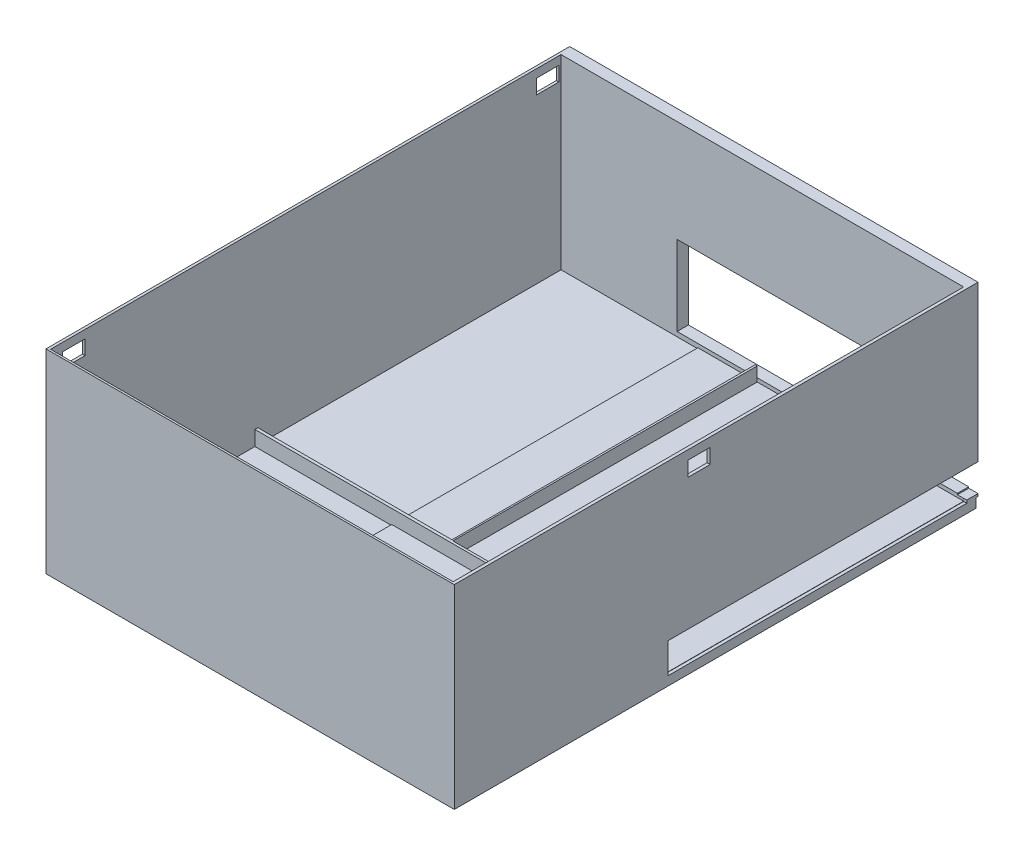
SolidWorks part; units mm, degrees
ref_plane "Front Plane" through (0, 0, 0) normal (0, 0, 1) x (1, 0, 0)
ref_plane "Top Plane" through (0, 0, 0) normal (0, 1, 0) x (1, 0, 0)
ref_plane "Right Plane" through (0, 0, 0) normal (1, 0, 0) x (0, 0, -1)
sketch "Sketch1" plane through (0, 0, 0) normal (0, 1, 0) x (1, 0, 0)
  line L1 (-37.1465, 32.3865) -> (39.0132, 32.3865)
  line L2 (-37.1465, 32.3865) -> (-37.1465, -94.5463)
  line L3 (-37.1465, -94.5463) -> (39.0132, -94.5463)
  line L4 (39.0132, 32.3865) -> (39.0132, -94.5463)
  dimension "D1" = 39.0132
  dimension "D2" = 37.1465
  dimension "D3" = 32.3865
  dimension "D4" = 94.5463
extrude "Boss-Extrude1" add sketch "Sketch1" along normal blind 2.54
sketch "Sketch2" plane through (0, 0, 0) normal (0, 1, 0) x (1, 0, 0)
  line L0 (-17.1137, 32.3865) -> (-19.5757, 32.3865)
  line L1 (-19.5757, 32.3865) -> (-19.5757, -53.9937)
  line L2 (39.0132, 32.3865) -> (-37.1465, 32.3865) construction
  line L3 (-19.5757, -53.9937) -> (39.0132, -53.9937)
  line L4 (-17.1137, 32.3865) -> (-17.1137, -51.9925)
  line L5 (39.0132, -51.9925) -> (-17.1137, -51.9925)
  line L6 (39.0132, -94.5463) -> (39.0132, 32.3865) construction
  line L7 (39.0132, -94.5463) -> (39.0132, 32.3865) construction
  line L8 (39.0132, -53.9937) -> (39.0132, -51.9925)
  dimension "D1" = 17.1137
  dimension "D2" = 19.5757
  dimension "D3" = 51.9925
  dimension "D4" = 53.9937
sketch "Sketch7" plane through (0, 2.54, 0) normal (0, 1, 0) x (1, 0, 0)
  line L0 (-37.1465, 32.3865) -> (-37.1465, -94.5463)
  line L1 (-37.1465, -94.5463) -> (39.0132, -94.5463)
  line L2 (39.0132, -94.5463) -> (39.0132, 32.3865)
  line L4 (-37.1465, 32.3865) -> (-37.1465, 37.5149)
  line L5 (39.0132, 37.5149) -> (39.0132, 32.3865)
  line L6 (39.0132, 37.5149) -> (-37.1465, 37.5149)
  dimension "D1" = 132.0612
extrude "Boss-Extrude4" add sketch "Sketch7" along normal blind 38.1
shell "Shell1" thickness 2.54
sketch "Sketch12" plane through (0, 0, 0) normal (0, 1, 0) x (1, 0, 0)
  line L14 (-19.5757, -53.9937) -> (39.0132, -53.9937) construction
  line L15 (-17.7524, -53.9937) -> (39.0132, -53.9937)
  line L17 (39.0132, -53.9937) -> (39.0132, -53.3287)
  line L18 (39.0132, -53.9937) -> (39.0132, -51.9925) construction
  line L25 (39.0132, -53.3287) -> (-17.7524, -53.3287)
  line L27 (-18.2815, -53.9937) -> (-17.7524, -53.9937)
  line L28 (-17.7524, -53.3287) -> (-18.5357, -53.3287)
  line L29 (-18.5357, -53.3287) -> (-18.3447, 32.3865)
  line L30 (-17.1137, 32.3865) -> (-19.5757, 32.3865) construction
  line L31 (-18.3447, 32.3865) -> (-18.928, 32.3865)
  line L32 (-18.928, 32.3865) -> (-18.928, -53.9937)
  line L33 (-18.928, -53.9937) -> (-18.2815, -53.9937)
  dimension "D1" = 17.7524
  dimension "D2" = 18.2815
  dimension "D3" = 18.5357
  dimension "D4" = 18.928
  dimension "D5" = 53.3287
extrude "Boss-Extrude5" add sketch "Sketch12" along normal blind 6.35
ref_plane "Plane3" through (0, 0, -40.0549) normal (0, 0, -1) x (-1, 0, 0)
sketch "Sketch16" plane through (0, 0, -40.0549) normal (0, 0, -1) x (-1, 0, 0)
  line L0 (-39.0132, 40.64) -> (-39.0132, 0)
  line L1 (-39.0132, 0) -> (37.1465, 0)
  line L2 (-39.0132, 40.64) -> (37.1465, 40.64)
  line L3 (37.1465, 40.64) -> (37.1465, 0)
extrude "Cut-Extrude7" cut sketch "Sketch16" against normal blind 7.112
ref_plane "Plane4" through (0, 7.62, 0) normal (0, 1, 0) x (1, 0, 0)
sketch "Sketch17" plane through (0, 7.62, 0) normal (0, 1, 0) x (1, 0, 0)
  line L0 (-34.6065, 32.9429) -> (-34.6065, 29.8465)
  line L1 (-34.6065, 29.8465) -> (36.4732, 29.8465)
  line L2 (36.4732, 29.8465) -> (36.4732, 32.9429)
  line L3 (36.4732, 32.9429) -> (-34.6065, 32.9429)
extrude "Cut-Extrude8" cut sketch "Sketch17" against normal blind 4.064
sketch "Sketch19" plane through (0, 0, 0) normal (0, 1, 0) x (1, 0, 0)
  line L3 (-37.1465, 32.9429) -> (-37.1465, -94.5463)
  line L5 (-72.7979, 32.9429) -> (-72.7979, -94.5463)
  line L8 (-72.7979, -94.5463) -> (-37.1465, -94.5463)
  line L9 (-72.7979, 32.9429) -> (-37.1465, 32.9429)
  dimension "D2" = 72.7979
extrude "Boss-Extrude19" add sketch "Sketch19" along normal blind 2.286
ref_plane "Plane5" through (-39.6865, 0, 0) normal (-1, 0, 0) x (0, 0, 1)
sketch "Sketch26" plane through (-37.1465, 0, 0) normal (-1, 0, 0) x (0, 0, 1)
  line L1 (-32.9429, 40.64) -> (94.5463, 40.64)
  line L2 (-32.9429, 40.64) -> (-32.9429, 2.286)
  line L3 (-32.9429, 2.286) -> (94.5463, 2.286)
  line L4 (94.5463, 40.64) -> (94.5463, 2.286)
extrude "Cut-Extrude10" cut sketch "Sketch26" against normal blind 2.54
sketch "Sketch27" plane through (0, 0, 0) normal (0, 1, 0) x (1, 0, 0)
  line L0 (-34.6065, -94.5463) -> (-72.7979, -94.5463)
  line L1 (-72.7979, -94.5463) -> (-72.7979, 32.9429)
  line L2 (-34.6065, -94.5463) -> (-34.6065, -92.0063)
  line L4 (-34.6065, 29.8465) -> (-34.6065, -92.0063) construction
  line L5 (-34.6065, 32.3865) -> (-34.6065, -94.5463) construction
  line L6 (-34.6065, -92.0063) -> (-70.1044, -92.0063)
  line L8 (-72.7979, 32.9429) -> (-34.6065, 32.9429)
  line L10 (-34.6065, 29.8465) -> (-34.6065, 32.9429)
  line L11 (-34.6065, 29.8465) -> (-72.0805, 29.8465)
  line L12 (-72.0805, 29.8465) -> (-72.0805, -92.0063)
  line L13 (-72.0805, -92.0063) -> (-70.1044, -92.0063)
  dimension "D1" = 70.1044
  dimension "D2" = 72.0805
  dimension "D3" = 92.0063
  dimension "D4" = 29.8465
extrude "Boss-Extrude20" add sketch "Sketch27" along normal blind 40.64
sketch "Sketch28" plane through (0, 0, 0) normal (0, 1, 0) x (1, 0, 0)
  line L3 (-72.7979, -94.5463) -> (39.0132, -94.5463)
  line L6 (39.0132, -94.5463) -> (39.0132, -110.4832)
  line L11 (39.0132, -110.4832) -> (-72.7979, -110.4832)
  line L12 (-72.7979, -110.4832) -> (-72.7979, -94.5463)
  dimension "D2" = 110.4832
extrude "Boss-Extrude21" add sketch "Sketch28" along normal blind 2.54
ref_plane "Plane10" through (0, 0, 97.0863) normal (0, 0, 1) x (1, 0, 0)
sketch "Sketch34" plane through (0, 0, 97.0863) normal (0, 0, 1) x (1, 0, 0)
  line L1 (-72.7979, 40.64) -> (39.0132, 40.64)
  line L2 (-72.7979, 40.64) -> (-72.7979, 2.54)
  line L3 (-72.7979, 2.54) -> (39.0132, 2.54)
  line L4 (39.0132, 40.64) -> (39.0132, 2.54)
extrude "Cut-Extrude12" cut sketch "Sketch34" against normal blind 5.08
sketch "Sketch36" plane through (0, 0, 0) normal (0, 1, 0) x (1, 0, 0)
  line L0 (-72.7979, -92.0063) -> (-72.7979, -110.4832)
  line L1 (-72.7979, -110.4832) -> (39.0132, -110.4832)
  line L2 (39.0132, -110.4832) -> (39.0132, -92.0063)
  line L3 (39.0132, -92.0063) -> (36.4732, -92.0063)
  line L6 (36.4732, -92.0063) -> (36.4732, -108.8333)
  line L7 (36.4732, -108.8333) -> (-72.0805, -108.8333)
  line L8 (-72.0805, -92.0063) -> (-72.0805, -108.8333)
  line L9 (-72.7979, -92.0063) -> (-72.0805, -92.0063)
  dimension "D1" = 108.8333
extrude "Boss-Extrude23" add sketch "Sketch36" along normal blind 40.64
sketch "Sketch39" plane through (0, 0, 0) normal (0, 1, 0) x (1, 0, 0)
  line L0 (-19.5757, -53.9937) -> (-72.0805, -53.9937)
  line L1 (-72.0805, -53.9937) -> (-72.0805, -53.1862)
  line L2 (-72.0805, -92.0063) -> (-72.0805, 29.8465) construction
  line L7 (-72.0805, -108.8333) -> (-72.0805, 29.8465) construction
  line L8 (-72.0805, -53.1862) -> (-19.5757, -53.1862)
  line L9 (-19.5757, 32.3865) -> (-19.5757, -53.9937) construction
  line L22 (-19.5757, -53.9937) -> (-18.928, -53.9937)
  line L23 (-19.5757, -53.1862) -> (-18.928, -53.1862)
  line L25 (-18.928, 29.8465) -> (-18.928, -53.9937) construction
  line L26 (-18.928, -53.1862) -> (-18.928, -53.9937)
  dimension "D1" = 53.1862
extrude "Boss-Extrude24" add sketch "Sketch39" along normal blind 6.35
sketch "Sketch51" plane through (0, 40.64, 0) normal (0, 1, 0) x (1, 0, 0)
  line L0 (-34.6065, 32.9429) -> (-34.6065, 29.8465)
  line L1 (-34.6065, 29.8465) -> (-72.0805, 29.8465)
  line L2 (-72.0805, 29.8465) -> (-72.0805, -108.8333)
  line L6 (39.0132, 32.9429) -> (39.0132, -110.4832)
  line L7 (39.0132, -110.4832) -> (-72.7979, -110.4832)
  line L8 (-72.7979, -110.4832) -> (-72.7979, 32.9429)
  line L9 (-72.7979, 32.9429) -> (-34.6065, 32.9429)
  line L10 (39.0132, 32.9429) -> (38.1798, 32.9429)
  line L11 (36.4732, 32.9429) -> (39.0132, 32.9429) construction
  line L12 (38.1798, -109.5531) -> (38.1798, 32.9429)
  line L14 (-72.0805, -109.5531) -> (-72.0805, -108.8333)
  line L16 (-72.0805, -109.5531) -> (-72.0805, -109.9497)
  line L17 (-72.0805, -109.9497) -> (38.1798, -109.9497)
  line L18 (38.1798, -109.9497) -> (38.1798, -109.5531)
  dimension "D1" = 1.7066
  dimension "D2" = 142.496
  dimension "D3" = 142.8926
extrude "Boss-Extrude28" add sketch "Sketch51" along normal blind 12.7
sketch "Sketch52" plane through (0, 53.34, 0) normal (0, 1, 0) x (1, 0, 0)
  line L1 (-34.6065, 32.9429) -> (-72.7979, 32.9429) construction
  line L2 (-34.6065, 29.8465) -> (-34.6065, 32.9429) construction
  line L8 (38.1798, 32.9429) -> (38.1798, 29.8465)
  line L9 (38.1798, 32.9429) -> (38.1798, -109.9497) construction
  line L11 (38.1798, 32.9429) -> (-34.6065, 32.9429)
  line L12 (-34.6065, 29.8465) -> (38.1798, 29.8465)
  line L13 (-34.6065, 32.9429) -> (-39.7253, 32.9429)
  line L14 (-39.7253, 32.9429) -> (-39.7253, 29.8465)
  line L15 (-72.0805, 29.8465) -> (-34.6065, 29.8465) construction
  line L16 (-39.7253, 29.8465) -> (-34.6065, 29.8465)
  line L17 (39.0132, -110.4832) -> (39.0132, 32.9429) construction
  dimension "D1" = 78.7385
extrude "Boss-Extrude29" add sketch "Sketch52" against normal blind 27.94
ref_plane "Plane15" through (-75.3379, 0, 0) normal (-1, 0, 0) x (0, 0, 1)
sketch "Sketch54" plane through (-72.7979, 0, 0) normal (-1, 0, 0) x (0, 0, 1)
  line L0 (100.4953, 51.0887) -> (100.4953, 47.1068)
  line L1 (-29.2744, 51.0887) -> (-23.0672, 51.0887)
  line L2 (-29.2744, 51.0887) -> (-29.2744, 47.1068)
  line L3 (-29.2744, 47.1068) -> (-23.0672, 47.1068)
  line L4 (-23.0672, 51.0887) -> (-23.0672, 47.1068)
  line L5 (100.4953, 47.1068) -> (106.7025, 47.1068)
  line L6 (100.4953, 51.0887) -> (106.7025, 51.0887)
  line L7 (106.7025, 51.0887) -> (106.7025, 47.1068)
  line L8 (110.4832, 53.34) -> (110.4832, 0) construction
  line L11 (-32.9429, 53.34) -> (-32.9429, 0) construction
  line L12 (-32.9429, 53.34) -> (110.4832, 53.34) construction
  dimension "D1" = 3.7808
  dimension "D2" = 9.9879
  dimension "D3" = 2.2513
  dimension "D4" = 9.8757
  dimension "D5" = 6.2332
  dimension "D6" = 3.6685
extrude "Cut-Extrude20" cut sketch "Sketch54" against normal blind 15.24
ref_plane "Plane16" through (41.5532, 0, 0) normal (1, 0, 0) x (0, 0, -1)
sketch "Sketch55" plane through (41.5532, 0, 0) normal (1, 0, 0) x (0, 0, -1)
  line L8 (-46.5087, 50.8509) -> (-46.5087, 46.7892)
  line L9 (-46.5087, 50.8509) -> (-40.4044, 50.8509)
  line L10 (-40.4044, 50.8509) -> (-40.4044, 46.7892)
  line L11 (-40.4044, 46.7892) -> (-46.5087, 46.7892)
  dimension "D1" = 40.4044
  dimension "D2" = 50.8509
  dimension "D3" = 46.5087
  dimension "D5" = 46.7892
extrude "Cut-Extrude21" cut sketch "Sketch55" against normal blind 15.24
sketch "Sketch56" plane through (0, 40.64, 0) normal (0, 1, 0) x (1, 0, 0)
  line L0 (36.4732, 29.8465) -> (38.1798, 29.8465)
  line L1 (38.1798, 29.8465) -> (38.1798, -108.8333)
  line L2 (38.1798, 29.8465) -> (38.1798, -109.9497) construction
  line L3 (38.1798, -108.8333) -> (36.4732, -108.8333)
  line L4 (36.4732, -108.8333) -> (36.4732, 29.8465)
extrude "Cut-Extrude22" cut sketch "Sketch56" against normal blind 38.1
sketch "Sketch57" plane through (0, 0, -32.9429) normal (0, 0, -1) x (-1, 0, 0)
  line L0 (34.6065, 25.4) -> (40.285, 25.4)
  line L1 (40.285, 25.4) -> (40.285, 3.556)
  line L2 (40.285, 3.556) -> (34.6065, 3.556)
  line L3 (34.6065, 3.556) -> (34.6065, 25.4)
  line L4 (-36.4732, 3.556) -> (-36.4732, 25.4) construction
  dimension "D1" = 76.7582
extrude "Cut-Extrude23" cut sketch "Sketch57" against normal blind 38.1
sketch "Sketch58" plane through (39.0132, 0, 0) normal (1, 0, 0) x (0, 0, -1)
  line L0 (32.9429, 53.34) -> (32.9429, 2.54) construction
  line L6 (-43.8922, 50.8509) -> (-37.7871, 50.8509) construction
  line L31 (-51.9925, 3.2204) -> (32.3865, 3.2204)
  line L38 (-51.9925, 10.76) -> (32.9429, 10.76)
  line L39 (32.9429, 10.76) -> (32.9429, 3.9009)
  line L42 (-46.5087, 50.8509) -> (-40.4044, 50.8509) construction
  line L43 (-51.9925, 10.76) -> (-51.9925, 3.2204)
  line L44 (-46.5087, 46.7892) -> (-46.5087, 50.8509) construction
  line L45 (32.3865, 3.2204) -> (32.9429, 3.2204)
  line L46 (32.9429, 3.2204) -> (32.9429, 3.9009)
  dimension "D1" = 5.4838
  dimension "D2" = 40.0909
  dimension "D3" = 78.8953
  dimension "D4" = 46.95
  dimension "D8" = 47.6305
extrude "Cut-Extrude24" cut sketch "Sketch58" against normal blind 2.54
sketch "Sketch59" plane through (0, 40.64, 0) normal (0, 1, 0) x (1, 0, 0)
  line L3 (38.1798, -108.8333) -> (-72.0805, -108.8333)
  line L6 (-72.0805, -109.9497) -> (38.1798, -109.9497)
  line L7 (38.1798, -109.9497) -> (-72.0805, -109.9497) construction
  line L9 (38.1798, -108.8333) -> (38.1798, -109.9497)
  line L10 (-72.0805, -108.8333) -> (-72.0805, -109.9497)
extrude "Cut-Extrude25" cut sketch "Sketch59" against normal blind 38.1
sketch "Sketch61" plane through (0, 0, -29.8465) normal (0, 0, 1) x (1, 0, 0)
  line L0 (36.4732, 25.4) -> (38.1798, 25.4)
  line L1 (38.1798, 10.76) -> (38.1798, 53.34) construction
  line L2 (38.1798, 25.4) -> (38.1798, 10.76)
  line L3 (38.1798, 10.76) -> (36.4732, 10.76)
  line L4 (36.4732, 10.76) -> (36.4732, 25.4)
extrude "Cut-Extrude26" cut sketch "Sketch61" against normal blind 4.064
sketch "Sketch62" plane through (0, 3.2204, 0) normal (0, 1, 0) x (1, 0, 0)
  line L0 (38.1798, -51.9925) -> (39.0132, -51.9925)
  line L1 (39.0132, -51.9925) -> (39.0132, 29.9)
  line L2 (39.0132, -51.9925) -> (39.0132, 32.9429) construction
  line L3 (38.1798, 29.8465) -> (39.0132, 29.9)
  line L4 (38.1798, 29.8465) -> (38.1798, -51.9925)
  line L5 (38.1798, -51.9925) -> (38.1798, 29.8465) construction
  dimension "D1" = 0.0534
extrude "Cut-Extrude28" cut sketch "Sketch62" against normal blind 0.762
